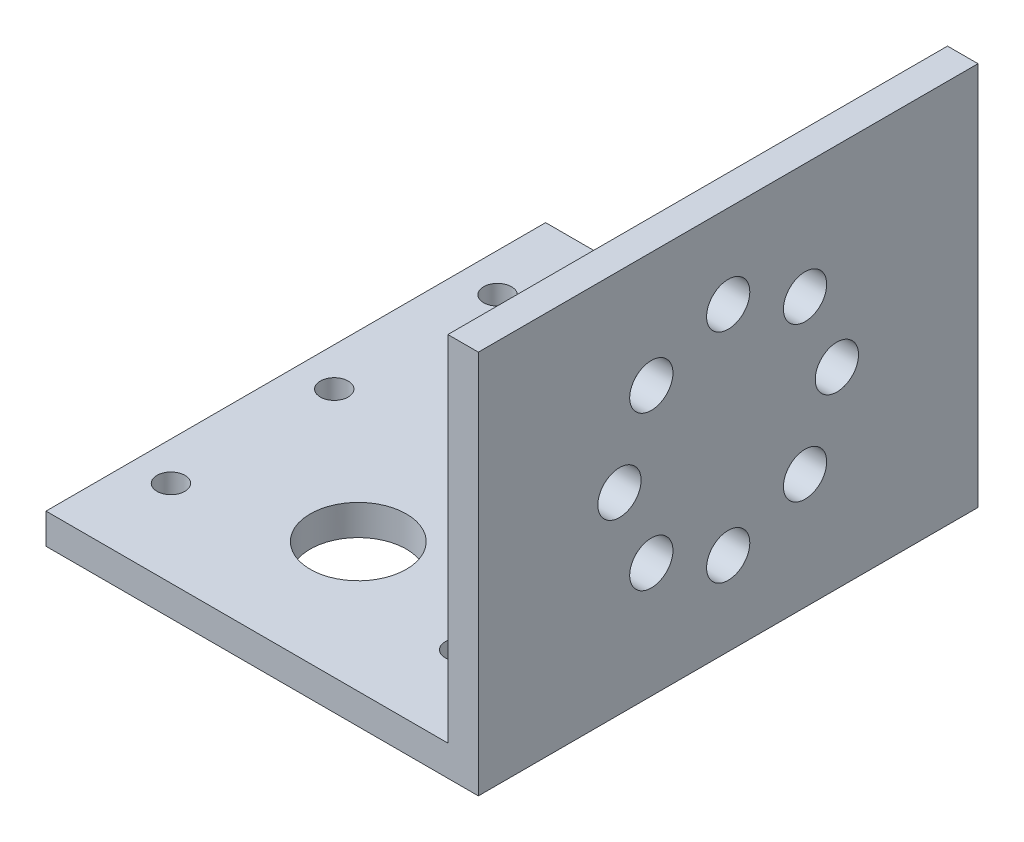
SolidWorks part; units mm, degrees
material "1060 Alloy"
ref_plane "Front Plane" through (0, 0, 0) normal (0, 0, 1) x (1, 0, 0)
ref_plane "Top Plane" through (0, 0, 0) normal (0, 1, 0) x (1, 0, 0)
ref_plane "Right Plane" through (0, 0, 0) normal (1, 0, 0) x (0, 0, -1)
sketch "Sketch1" plane through (0, 0, 0) normal (0, 0, 1) x (1, 0, 0)
  line L0 (0, 0) -> (0, 36.825)
  line L1 (0, 36.825) -> (3.175, 36.825)
  line L2 (3.175, 36.825) -> (3.175, -3.175)
  line L3 (3.175, -3.175) -> (-41.825, -3.175)
  line L4 (-41.825, -3.175) -> (-41.825, 0)
  line L15 (-41.825, 0) -> (0, 0)
  dimension "D1" = 3.175
  dimension "D2" = 3.175
  dimension "D3" = 45
  dimension "D4" = 40
extrude "Boss-Extrude1" add sketch "Sketch1" along normal blind 52
sketch "Sketch2" plane through (3.175, 0, 0) normal (1, 0, 0) x (0, 0, -1)
  line L0 (-26, 36.825) -> (-26, -3.175) construction
  line L1 (-52, 36.825) -> (0, 36.825) construction
  line L2 (-52, -3.175) -> (0, -3.175) construction
  circle A0 centre (-26, 28.1387) radius 2
  circle A1 centre (-26, 16.825) radius 11.3137 construction
  circle A2 centre (-18, 24.825) radius 2
  circle A3 centre (-14.6863, 16.825) radius 2
  circle A4 centre (-18, 8.825) radius 2
  circle A5 centre (-26, 5.5113) radius 2
  circle A6 centre (-34, 8.825) radius 2
  circle A7 centre (-37.3137, 16.825) radius 2
  circle A8 centre (-34, 24.825) radius 2
  point P27 (-26, 16.825)
  dimension "D1" = 4
  dimension "D2" = 16
  dimension "D3" = 8
sketch "Sketch3" plane through (0, -3.175, 0) normal (0, -1, 0) x (-1, 0, 0)
  line L2 (41.825, 0) -> (-3.175, 0) construction
  line L3 (41.825, -52) -> (41.825, 0) construction
  circle A0 centre (7.825, -43) radius 1.25 construction
  circle A1 centre (37.825, -43) radius 1.25 construction
  circle A2 centre (37.825, -26) radius 1.25 construction
  circle A3 centre (37.825, -9) radius 1.25 construction
  circle A4 centre (7.825, -26) radius 1.25 construction
  circle A5 centre (7.825, -9) radius 1.25 construction
  circle A6 centre (22.825, -38.5) radius 5
  dimension "D1" = 2.5
  dimension "D6" = 10
  dimension "D7" = 4.5
  dimension "D2" = 9
  dimension "D3" = 4
  dimension "D8" = 15
  dimension "D4" = 2
  dimension "D5" = 3
extrude "Cut-Extrude2" cut sketch "Sketch3" against normal through all
hole_wizard "M2.5 Clearance Hole1" positions "Sketch4" profile "Sketch5" hole size "M2.5" standard "ISO" end condition through all
sketch "Sketch4" plane through (0, -3.175, 0) normal (0, -1, 0) x (-1, 0, 0)
  point P0 (7.825, -9)
  point P3 (37.825, -9)
  point P6 (7.825, -26)
  point P9 (37.825, -26)
  point P12 (37.825, -43)
  point P15 (7.825, -43)
sketch "Sketch5" plane through (-7.825, -3.175, 9) normal (1, 0, 0) x (0, 0, -1)
  line L0 (0, 0) -> (0, 40)
  line L1 (0, 40) -> (1.45, 40)
  line L2 (1.45, 40) -> (1.45, 0)
  line L5 (1.45, 0) -> (0, 0)
  line L11 (0, -6.35) -> (0, 107.95) construction
  dimension "Thru Hole Dia." = 2.9
  dimension "Thru Hole Depth" = 40
hole_wizard "M4 Clearance Hole1" positions "Sketch6" profile "Sketch7" hole size "M4" standard "ISO" end condition through all
sketch "Sketch6" plane through (3.175, 0, 0) normal (1, 0, 0) x (0, 0, -1)
  point P0 (-26, 28.1387)
  point P3 (-18, 24.825)
  point P6 (-14.6863, 16.825)
  point P9 (-18, 8.825)
  point P12 (-26, 5.5113)
  point P15 (-34, 8.825)
  point P18 (-37.3137, 16.825)
  point P21 (-34, 24.825)
sketch "Sketch7" plane through (3.175, 28.1387, 26) normal (0, 1, 0) x (0, 0, -1)
  line L0 (0, 0) -> (0, 45)
  line L1 (0, 45) -> (2.25, 45)
  line L2 (2.25, 45) -> (2.25, 0)
  line L5 (2.25, 0) -> (0, 0)
  line L11 (0, -6.35) -> (0, 107.95) construction
  dimension "Thru Hole Dia." = 4.5
  dimension "Thru Hole Depth" = 45
